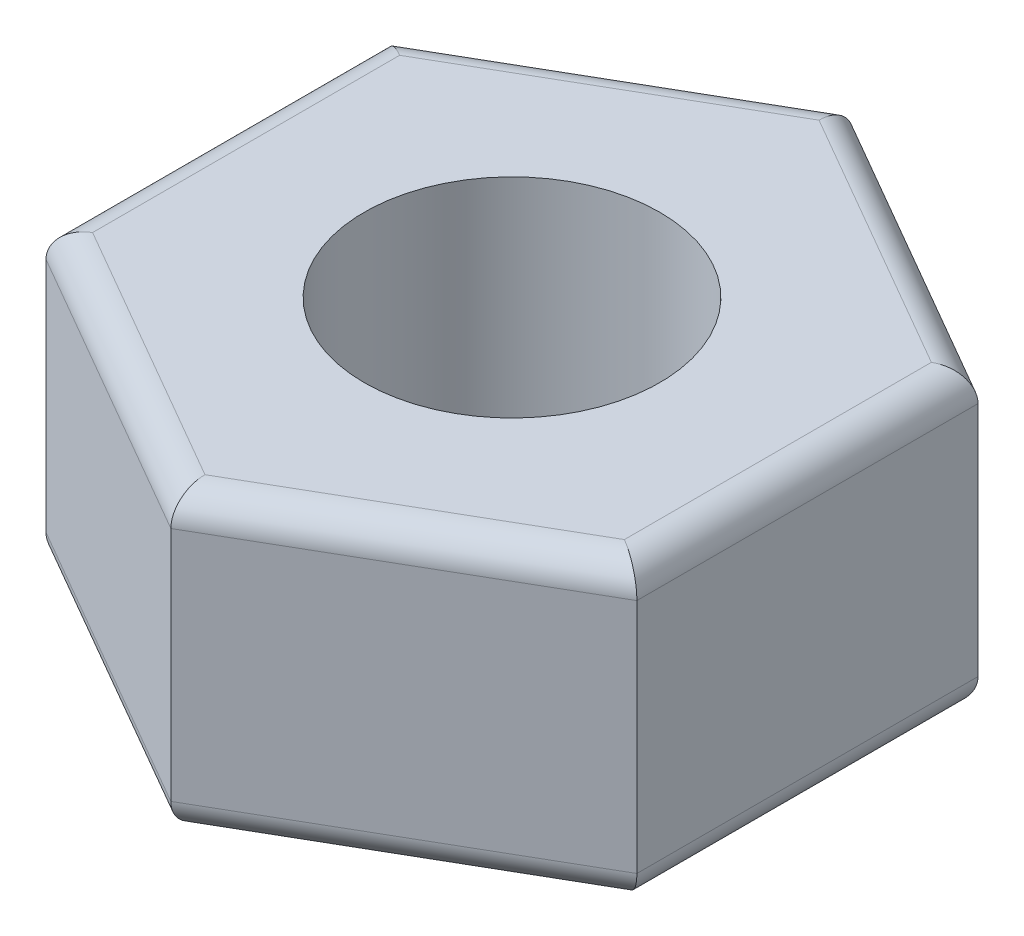
SolidWorks part; units mm, degrees
material "AISI 1020"
ref_plane "Front Plane" through (0, 0, 0) normal (0, 0, 1) x (1, 0, 0)
ref_plane "Top Plane" through (0, 0, 0) normal (0, 1, 0) x (1, 0, 0)
ref_plane "Right Plane" through (0, 0, 0) normal (1, 0, 0) x (0, 0, -1)
sketch "Sketch1" plane through (0, 0, 0) normal (0, 1, 0) x (1, 0, 0)
  line L1 (0, 4.6188) -> (-4, 2.3094)
  line L2 (-4, 2.3094) -> (-4, -2.3094)
  line L3 (-4, -2.3094) -> (0, -4.6188)
  line L4 (0, -4.6188) -> (4, -2.3094)
  line L5 (4, -2.3094) -> (4, 2.3094)
  line L6 (4, 2.3094) -> (0, 4.6188)
  circle A0 centre (0, 0) radius 2
  circle A1 centre (0, 0) radius 4 construction
  dimension "D1" = 4
  dimension "D2" = 8
extrude "Boss-Extrude1" add sketch "Sketch1" along normal blind 4
cosmetic thread "Cosmetic Thread1" parameters "D1"=4, "D2"=5.4
fillet "Fillet1" radius 0.4 12 edges at (2, 0, -3.4641) (4, 0, 0) (2, 0, 3.4641) (-2, 0, -3.4641) (-4, 0, 0) (-2, 0, 3.4641) (-4, 4, 0) (-2, 4, -3.4641) (2, 4, -3.4641) (4, 4, 0) (2, 4, 3.4641) (-2, 4, 3.4641)
